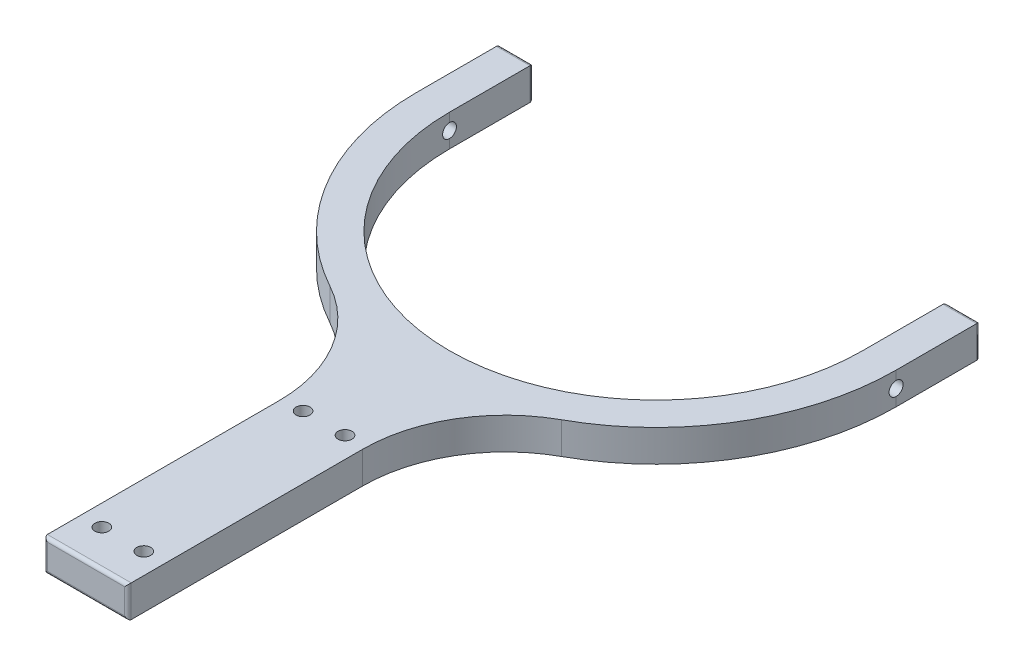
SolidWorks part; units mm, degrees
ref_plane "Plano frontal" through (0, 0, 0) normal (0, 0, 1) x (1, 0, 0)
ref_plane "Plano superior" through (0, 0, 0) normal (0, 1, 0) x (1, 0, 0)
ref_plane "Plano direito" through (0, 0, 0) normal (1, 0, 0) x (0, 0, -1)
sketch "Esboço2" plane through (0, 0, 0) normal (0, 1, 0) x (1, 0, 0)
  line L2 (-25, -200) -> (-25, -340)
  line L3 (-25, -340) -> (25, -340)
  line L4 (25, -340) -> (25, -200)
  line L5 (-143.2, 0) -> (-143.2, 50)
  line L6 (-143.2, 50) -> (-123.2, 50)
  line L7 (-123.2, 50) -> (-123.2, 0)
  line L8 (123.2, 0) -> (123.2, 50)
  line L9 (123.2, 50) -> (143.2, 50)
  line L10 (143.2, 50) -> (143.2, 0)
  arc A0 (-123.2, 0) -> (123.2, 0) centre (0, 0) ccw
  arc A1 (-143.2, 0) -> (-69.0612, -125.4464) centre (0, 0) ccw
  arc A2 (143.2, 0) -> (69.0612, -125.4464) centre (0, 0) cw
  arc A3 (69.0612, -125.4464) -> (25, -200) centre (110.1047, -200) ccw
  arc A4 (-25, -200) -> (-69.0612, -125.4464) centre (-110.1047, -200) ccw
  dimension "D1" = 123.2
  dimension "D4" = 50
  dimension "D2" = 20
  dimension "D3" = 20
  dimension "D5" = 50
  dimension "D6" = 50
  dimension "D7" = 140
  dimension "D8" = 25
  dimension "D9" = 340
extrude "Ressalto-extrusão1" add sketch "Esboço2" along normal blind 19
fillet "Filete2" radius 2 4 edges at (-123.2, 9.5, -50) (-133.2, 0, -50) (-143.2, 9.5, -50) (-133.2, 19, -50)
fillet "Filete3" radius 2 4 edges at (123.2, 9.5, -50) (133.2, 0, -50) (133.2, 19, -50) (143.2, 9.5, -50)
fillet "Filete4" radius 2 4 edges at (25, 9.5, 340) (0, 0, 340) (-25, 9.5, 340) (0, 19, 340)
sketch "Esboço5" plane through (0, 19, 0) normal (0, 1, 0) x (1, 0, 0)
  line L0 (-25, -200) -> (-25, -338) construction
  line L1 (-25, -338) -> (25, -338) construction
  point P0 (-12.5, -318)
  point P1 (12.5, -318)
  point P2 (12.5, -198)
  point P3 (-12.5, -198)
  dimension "D1" = 12.5
  dimension "D2" = 25
  dimension "D3" = 120
  dimension "D4" = 20
hole_wizard "Furo roscado para conduíte de M8x1.252" positions "3DSketch4" profile "Esboço7" tap size "M8x1.25" standard "Helicoil® Metric" end condition through all
sketch3d "3DSketch4"
  point P0 (-12.5, 19, 318)
  point P4 (12.5, 19, 318)
  point P7 (12.5, 19, 198)
  point P10 (-12.5, 19, 198)
sketch "Esboço7" plane through (-12.5, 19, 318) normal (1, 0, 0) x (0, 0, 1)
  line L0 (0, 0) -> (0, 19)
  line L1 (0, 19) -> (4.15, 19)
  line L2 (4.15, 19) -> (4.15, 0)
  line L5 (4.15, 0) -> (0, 0)
  line L11 (0, -6.35) -> (0, 107.95) construction
  dimension "Thru Tap Drill Dia." = 8.3
  dimension "Thru Tap Drill Depth" = 19
cosmetic thread "Rosca de furo3" parameters "D1"=19, "D2"=9.787
cosmetic thread "Rosca de furo4" parameters "D1"=19, "D2"=9.787
cosmetic thread "Rosca de furo5" parameters "D1"=19, "D2"=9.787
cosmetic thread "Rosca de furo6" parameters "D1"=19, "D2"=9.787
sketch "Esboço8" plane through (143.2, 0, 0) normal (1, 0, 0) x (0, 0, -1)
  line L0 (0, 19) -> (0, 0) construction
  point P0 (0, 9.5)
sketch "Esboço10" plane through (-143.2, 0, 0) normal (-1, 0, 0) x (0, 0, 1)
  line L0 (0, 19) -> (0, 0) construction
  point P0 (0, 9.5)
hole_wizard "Furo roscado para conduíte de M8x1.251" positions "3DSketch6" profile "Esboço11" tap size "M8x1.25" standard "Helicoil® Metric"
sketch3d "3DSketch6"
  point P0 (143.2, 9.5, 0)
  point P3 (-143.2, 9.5, 0)
sketch "Esboço11" plane through (143.2, 9.5, 0) normal (0, 1, 0) x (0, 0, -1)
  line L0 (0, 0) -> (0, 27.4936)
  line L1 (0, 27.4936) -> (4.15, 25)
  line L2 (4.15, 25) -> (4.15, 0)
  line L5 (4.15, 0) -> (0, 0)
  line L10 (0, 27.4936) -> (-4.15, 25) construction
  line L11 (0, -6.35) -> (0, 107.95) construction
  dimension "Tap Drill Dia." = 8.3
  dimension "Tap Drill Depth" = 25
  dimension "Drill Angle" = 118
cosmetic thread "Rosca de furo1" parameters "D1"=25, "D2"=9.787
cosmetic thread "Rosca de furo2" parameters "D1"=25, "D2"=9.787
